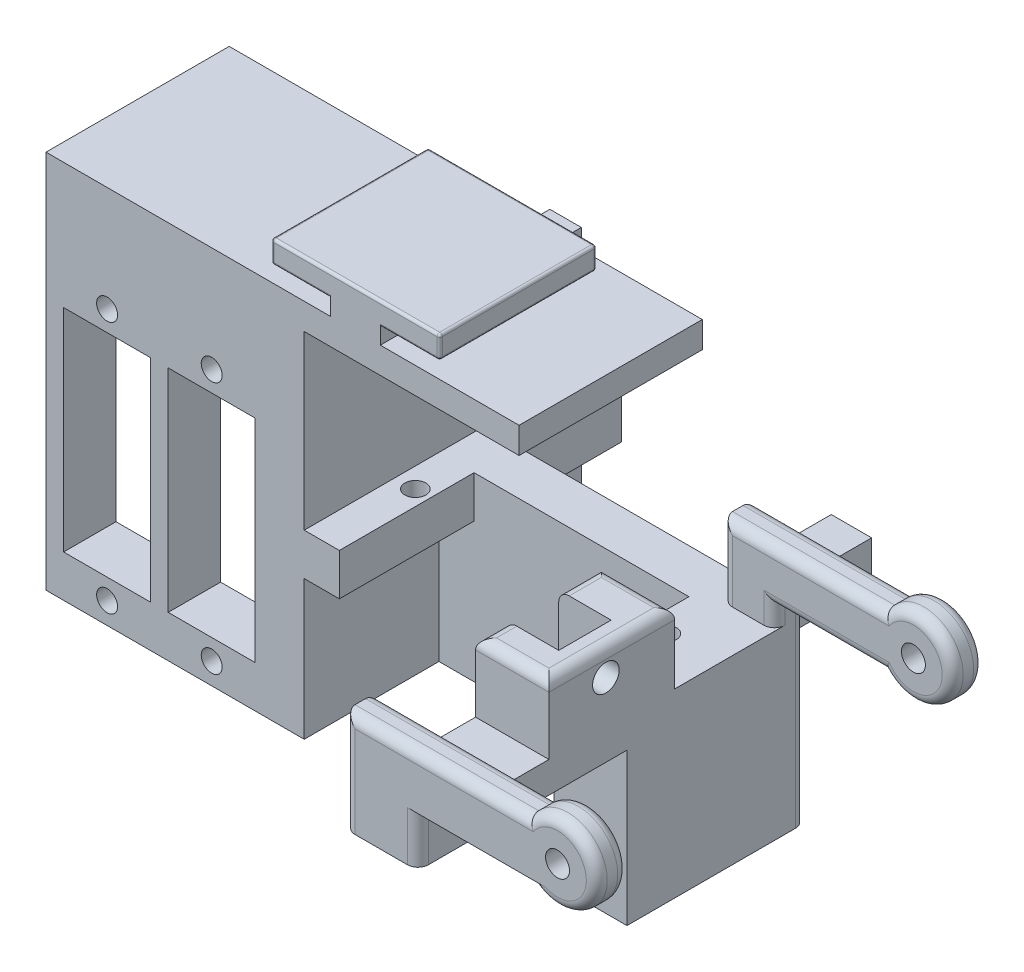
SolidWorks part; units mm, degrees
ref_plane "Front Plane" through (0, 0, 0) normal (0, 0, 1) x (1, 0, 0)
ref_plane "Top Plane" through (0, 0, 0) normal (0, 1, 0) x (1, 0, 0)
ref_plane "Right Plane" through (0, 0, 0) normal (1, 0, 0) x (0, 0, -1)
sketch "Sketch1" plane through (0, 0, 0) normal (0, 0, 1) x (1, 0, 0)
  line L1 (-10.82, 18.1) -> (10.82, 18.1)
  line L2 (-10.82, 18.1) -> (-10.82, -18.1)
  line L3 (-10.82, -18.1) -> (10.82, -18.1)
  line L4 (10.82, 18.1) -> (10.82, -18.1)
  line L5 (-10.82, 18.1) -> (10.82, -18.1) construction
  line L6 (-10.82, -18.1) -> (10.82, 18.1) construction
  point P0 (0, 0)
  dimension "D1" = 21.64
  dimension "D2" = 36.2
extrude "Center Column" add sketch "Sketch1" along normal mid plane 5
sketch "Sketch2" plane through (-10.82, 0, 0) normal (-1, 0, 0) x (0, 0, 1)
  line L0 (-2.5, 18.1) -> (-14.98, 18.1)
  line L1 (-14.98, 18.1) -> (-14.98, 15.6)
  line L2 (-14.98, 15.6) -> (-10.5, 15.6)
  line L3 (-10.5, 15.6) -> (-2.5, 10.98)
  line L4 (-2.5, 18.1) -> (-2.5, -18.1) construction
  line L6 (-2.5, 10.98) -> (2.5, 10.98)
  line L7 (2.5, 18.1) -> (2.5, -18.1) construction
  line L8 (2.5, 10.98) -> (2.5, 18.1)
  line L9 (2.5, 18.1) -> (-2.5, 18.1)
  dimension "D1" = 12.48
  dimension "D2" = 2.5
  dimension "D3" = 4.48
  dimension "D4" = 7.12
extrude "Column Cap" add sketch "Sketch2" against normal blind 55.14
sketch "Sketch5" plane through (0, 0, 2.5) normal (0, 0, 1) x (1, 0, 0)
  line L0 (16.33, 18.1) -> (21.08, 18.1)
  line L1 (44.32, 18.1) -> (-10.82, 18.1) construction
  line L2 (21.08, 18.1) -> (21.08, 19.6)
  line L3 (21.08, 19.6) -> (26.74, 19.6)
  line L4 (26.74, 19.6) -> (26.74, 21.75)
  line L5 (26.74, 21.75) -> (10.67, 21.75)
  line L6 (10.67, 21.75) -> (10.67, 19.6)
  line L7 (10.67, 19.6) -> (16.33, 19.6)
  line L8 (16.33, 19.6) -> (16.33, 18.1)
  dimension "D1" = 4.75
  dimension "D2" = 5.66
  dimension "D3" = 5.66
  dimension "D4" = 2.15
  dimension "D5" = 1.5
  dimension "D6" = 2.15
  dimension "D7" = 27.15
extrude "Attachment Block" add sketch "Sketch5" against normal blind 14.98
sketch "Sketch6" plane through (10.82, 0, 0) normal (1, 0, 0) x (0, 0, -1)
  line L0 (-2.5, -18.1) -> (-2.5, -3.6)
  line L1 (-2.5, -18.1) -> (-2.5, 10.98) construction
  line L2 (-2.5, -3.6) -> (2.5, -3.6)
  line L3 (2.5, -18.1) -> (2.5, 10.98) construction
  line L4 (2.5, -3.6) -> (2.5, -18.1)
  line L5 (2.5, -18.1) -> (-2.5, -18.1)
  dimension "D1" = 14.5
extrude "Central Extrusion" add sketch "Sketch6" along normal blind 33.792
sketch "Sketch7" plane through (0, 0, -2.5) normal (0, 0, -1) x (-1, 0, 0)
  line L0 (-10.82, -3.6) -> (-10.82, -0.8181)
  line L1 (-10.82, -3.6) -> (-10.82, 10.98) construction
  line L4 (-34.92, -0.8181) -> (-10.82, -0.8181)
  line L6 (-44.612, -18.1) -> (-10.82, -18.1)
  line L7 (10.82, -18.1) -> (-44.612, -18.1) construction
  line L8 (-10.82, -18.1) -> (-10.82, -3.6)
  line L10 (-44.612, -3.6) -> (-10.82, -3.6) construction
  line L11 (-34.92, -0.8181) -> (-44.612, -0.8181)
  line L12 (-44.612, -0.8181) -> (-44.612, -18.1)
  line L13 (-44.612, -18.1) -> (-40.254, -18.1)
  dimension "D1" = 24.1
  dimension "D2" = 2.7819
  dimension "D3" = 4.358
extrude "Wing Extrusion" add sketch "Sketch7" along normal mid plane 0.89
sketch "Sketch10" plane through (0, 0, -2.945) normal (0, 0, -1) x (-1, 0, 0)
  line L0 (-10.82, -0.8181) -> (-10.82, -9.8181)
  line L1 (-10.82, -9.8181) -> (-14.67, -9.8181)
  line L2 (-14.67, -9.8181) -> (-14.67, -0.8181)
  line L3 (-10.82, -0.8181) -> (-44.612, -0.8181) construction
  line L4 (-14.67, -0.8181) -> (-10.82, -0.8181)
  dimension "D1" = 9
  dimension "D2" = 3.85
extrude "Servo Tab Extrusion" add sketch "Sketch10" along normal blind 9.48
sketch "Sketch11" plane through (0, 0, -2.945) normal (0, 0, -1) x (-1, 0, 0)
  line L0 (-44.612, -0.8181) -> (-44.612, -18.1)
  line L1 (-14.67, -0.8181) -> (-44.612, -0.8181) construction
  line L2 (-44.612, -18.1) -> (-10.82, -18.1) construction
  line L3 (-44.612, -18.1) -> (-34.67, -18.1)
  line L4 (-34.67, -18.1) -> (-34.67, -0.8181)
  line L5 (-34.67, -0.8181) -> (-44.612, -0.8181)
  dimension "D1" = 20
  dimension "D2" = 0
extrude "Front Tab Extrusion" add sketch "Sketch11" along normal blind 11.63
sketch "Sketch15" plane through (0, 0, -2.055) normal (0, 0, 1) x (1, 0, 0)
  line L0 (37.612, -3.6) -> (47.612, -3.6)
  line L1 (10.82, -3.6) -> (44.612, -3.6) construction
  line L2 (47.612, -3.6) -> (47.612, 5.9)
  line L3 (47.612, 5.9) -> (37.612, 5.9)
  line L4 (37.612, 5.9) -> (37.612, -3.6)
  dimension "D1" = 7
  dimension "D2" = 10
  dimension "D3" = 9.5
extrude "Center Block" add sketch "Sketch15" along normal blind 12
sketch "Sketch16" plane through (37.612, 0, 0) normal (-1, 0, 0) x (0, 0, 1)
  line L0 (2.009, 5.9) -> (2.009, 0.47)
  line L1 (9.945, 5.9) -> (-2.055, 5.9) construction
  line L2 (2.009, 0.47) -> (7.009, 0.47)
  line L3 (7.009, 0.47) -> (7.009, 5.9)
  line L4 (2.009, 5.9) -> (7.009, 5.9)
  line L5 (-2.055, 5.9) -> (-2.055, -0.8181) construction
  dimension "D1" = 4.064
  dimension "D2" = 5
  dimension "D3" = 5.43
extrude "Center Chasm" cut sketch "Sketch16" against normal blind 5
sketch "Sketch17" plane through (42.612, 0, 0) normal (-1, 0, 0) x (0, 0, 1)
  line L0 (7.009, 5.9) -> (2.009, 5.9) construction
  line L1 (2.009, 5.9) -> (2.009, 0.47) construction
  circle A0 centre (4.509, 3.4) radius 1.27
  dimension "D1" = 2.54
  dimension "D2" = 2.5
  dimension "D3" = 2.5
extrude "Center Hole" cut sketch "Sketch17" against normal through all
sketch "Sketch18" plane through (0, 0, 9.945) normal (0, 0, 1) x (1, 0, 0)
  line L1 (47.612, -3.6) -> (47.612, 5.9) construction
  line L2 (47.612, -0.6488) -> (37.612, -0.6488)
  line L3 (37.612, 5.9) -> (37.612, -3.6) construction
  line L4 (37.612, -0.6488) -> (37.612, -3.6)
  line L6 (37.612, -3.6) -> (47.612, -3.6)
  line L7 (47.612, -3.6) -> (47.612, -0.6488)
  dimension "D1" = 2.9512
extrude "Holder Arm" add sketch "Sketch18" along normal blind 12.5
sketch "Sketch19" plane through (0, -0.6488, 0) normal (0, 1, 0) x (1, 0, 0)
  line L1 (37.612, -22.445) -> (37.612, -9.945) construction
  line L7 (37.612, -19.445) -> (37.612, -22.445)
  line L8 (37.612, -22.445) -> (47.612, -22.445)
  line L11 (37.612, -19.445) -> (47.612, -19.445)
  line L12 (47.612, -19.445) -> (47.612, -22.445)
  line L13 (47.612, -22.445) -> (47.612, -9.945) construction
  dimension "D1" = 3
extrude "Elbow Extrusion" add sketch "Sketch19" along normal blind 6.78
sketch "Sketch27" plane through (47.612, 0, 0) normal (1, 0, 0) x (0, 0, -1)
  line L0 (-22.445, 6.1312) -> (-22.445, 1.1312)
  line L1 (-22.445, -3.6) -> (-22.445, 6.1312) construction
  line L2 (-22.445, 1.1312) -> (-19.445, 1.1312)
  line L3 (-19.445, 6.1312) -> (-19.445, -0.6488) construction
  line L4 (-19.445, 1.1312) -> (-19.445, 6.1312)
  line L5 (-19.445, 6.1312) -> (-22.445, 6.1312)
  dimension "D1" = 5
extrude "Forearm Extrusion" add sketch "Sketch27" along normal blind 7.874
sketch "Sketch28" plane through (0, 0, 22.445) normal (0, 0, 1) x (1, 0, 0)
  circle A0 centre (57.932, 3.6312) radius 1.143
  circle A1 centre (57.932, 3.6312) radius 3.75
  dimension "D1" = 2.286
  dimension "D4" = 7.5
  dimension "D2" = 20.32
  dimension "D3" = 2.5
extrude "Hand Extrusion" add sketch "Sketch28" against normal up to surface (3 mm away) up to face at (46.9033, 2.2045, 19.445)
sketch "Sketch23" plane through (0, -0.8181, 0) normal (0, 1, 0) x (1, 0, 0)
  line L1 (44.612, 14.575) -> (39.612, 14.575)
  line L2 (44.612, 14.575) -> (44.612, 11.575)
  line L3 (44.612, 11.575) -> (39.612, 11.575)
  line L4 (39.612, 14.575) -> (39.612, 11.575)
  dimension "D1" = 5
  dimension "D2" = 3
extrude "Right Elbow Extrusion" add sketch "Sketch23" along normal blind 6.902
sketch "Sketch24" plane through (44.612, 0, 0) normal (1, 0, 0) x (0, 0, -1)
  line L0 (11.575, 6.0839) -> (14.575, 6.0839)
  line L1 (14.575, 6.0839) -> (14.575, 1.0839)
  line L2 (14.575, 6.0839) -> (14.575, -18.1) construction
  line L3 (14.575, 1.0839) -> (11.575, 1.0839)
  line L4 (11.575, 6.0839) -> (11.575, -0.8181) construction
  line L5 (11.575, 1.0839) -> (11.575, 6.0839)
  dimension "D1" = 5
extrude "Right Forearm Extrusion" add sketch "Sketch24" along normal blind 11
sketch "Sketch25" plane through (0, 0, -14.575) normal (0, 0, -1) x (-1, 0, 0)
  line L1 (-34.67, -18.1) -> (-34.67, -0.8181) construction
  circle A0 centre (-57.87, 3.5839) radius 1.143
  circle A1 centre (-57.87, 3.5839) radius 3.75
  dimension "D2" = 2.286
  dimension "D4" = 7.5
  dimension "D1" = 23.2
  dimension "D3" = 2.5
extrude "Right Hand" add sketch "Sketch25" against normal up to surface (3 mm away) up to face at (46.612, 2.1166, -11.575)
sketch "Sketch26" plane through (0, 0, -2.5) normal (0, 0, -1) x (-1, 0, 0)
  line L0 (10.82, 10.98) -> (10.82, -18.1) construction
  line L1 (0.84, 6.1) -> (9.14, 6.1)
  line L2 (0.84, 6.1) -> (0.84, -14.1)
  line L3 (0.84, -14.1) -> (9.14, -14.1)
  line L4 (9.14, 6.1) -> (9.14, -14.1)
  line L5 (-9.14, 6.1) -> (-0.84, 6.1)
  line L6 (-9.14, 6.1) -> (-9.14, -14.1)
  line L7 (-9.14, -14.1) -> (-0.84, -14.1)
  line L8 (-0.84, 6.1) -> (-0.84, -14.1)
  line L9 (10.82, 10.98) -> (-10.82, 10.98) construction
  circle A0 centre (-4.99, 8.05) radius 1
  circle A1 centre (4.99, 8.05) radius 1
  circle A2 centre (-4.99, -16.05) radius 1
  circle A3 centre (4.99, -16.05) radius 1
  dimension "D9" = 2
  dimension "D10" = 2
  dimension "D11" = 2
  dimension "D12" = 2
  dimension "D1" = 1.68
  dimension "D2" = 4.88
  dimension "D3" = 20.2
  dimension "D4" = 8.3
  dimension "D5" = 1.68
  dimension "D6" = 8.3
  dimension "D7" = 4.88
  dimension "D8" = 20.2
  dimension "D13" = 4.15
  dimension "D14" = 1.95
  dimension "D15" = 1.95
  dimension "D16" = 4.15
  dimension "D17" = 1.95
  dimension "D18" = 4.15
  dimension "D19" = 1.95
  dimension "D20" = 4.15
extrude "Rear Servo Mounts" cut sketch "Sketch26" against normal through all
sketch "Sketch29" plane through (10.82, 0, 0) normal (1, 0, 0) x (0, 0, -1)
  line L1 (-2.5, 10.98) -> (19.745, 10.98)
  line L2 (2.945, -18.1) -> (19.745, -18.1)
  line L3 (19.745, -18.1) -> (19.745, 10.98)
  line L4 (-2.5, 10.98) -> (-2.5, -18.1)
  line L5 (-2.5, -18.1) -> (2.945, -18.1)
  dimension "D2" = 16.8
extrude "New Back" add sketch "Sketch29" along normal blind 3
sketch "Sketch30" plane through (0, -18.1, 0) normal (0, -1, 0) x (1, 0, 0)
  line L10 (10.82, -19.745) -> (13.82, -19.745)
  line L11 (10.82, -19.745) -> (13.82, -19.745)
  line L12 (13.82, -19.745) -> (13.82, -2.945)
  line L13 (13.82, -19.745) -> (13.82, -2.945)
  line L14 (44.612, 2.5) -> (-10.82, 2.5)
  line L19 (-10.82, 2.5) -> (-10.82, -2.5)
  line L20 (-10.82, -2.5) -> (10.82, -2.5)
  line L21 (10.82, -2.5) -> (10.82, -19.745)
  line L24 (13.82, -2.945) -> (34.67, -2.945)
  line L25 (34.67, -2.945) -> (34.67, -14.575)
  line L26 (34.67, -14.575) -> (44.612, -14.575)
  line L27 (44.612, -14.575) -> (44.612, 2.5)
  line L28 (44.612, 2.5) -> (-10.82, 2.5)
  line L33 (-10.82, 2.5) -> (-10.82, -2.5)
  line L34 (-10.82, -2.5) -> (10.82, -2.5)
  line L35 (10.82, -2.5) -> (10.82, -19.745)
  line L38 (13.82, -2.945) -> (34.67, -2.945)
  line L39 (34.67, -2.945) -> (34.67, -14.575)
  line L40 (34.67, -14.575) -> (44.612, -14.575)
  line L41 (44.612, -14.575) -> (44.612, 2.5)
  dimension "D1" = 0
extrude "Bottom Support" add sketch "Sketch30" along normal blind 3
sketch "Sketch31" plane through (34.67, 0, 0) normal (-1, 0, 0) x (0, 0, 1)
  line L0 (-14.575, -0.8181) -> (-2.945, -0.8181)
  line L1 (-2.945, -0.8181) -> (-2.945, -21.1)
  line L2 (-2.945, -21.1) -> (-14.575, -21.1)
  line L3 (-14.575, -21.1) -> (-14.575, -0.8181)
extrude "Re-cut Central Cavity" cut sketch "Sketch31" against normal blind 3
sketch "Sketch32" plane through (14.67, 0, 0) normal (1, 0, 0) x (0, 0, -1)
  line L4 (2.945, -0.8181) -> (2.945, -9.8181)
  line L5 (2.945, -9.8181) -> (12.425, -9.8181)
  line L6 (12.425, -9.8181) -> (12.425, -0.8181)
  line L7 (12.425, -0.8181) -> (2.945, -0.8181)
  line L8 (2.945, -0.8181) -> (2.945, -9.8181)
  line L9 (2.945, -9.8181) -> (12.425, -9.8181)
  line L10 (12.425, -9.8181) -> (12.425, -0.8181)
  line L11 (12.425, -0.8181) -> (2.945, -0.8181)
  dimension "D1" = 0
extrude "Form Left Front-Rear Block" add sketch "Sketch32" along normal blind 3
sketch "Sketch33" plane through (0, 0, -2.945) normal (0, 0, -1) x (-1, 0, 0)
  line L0 (-37.67, -0.8181) -> (-37.67, -18.1)
  line L1 (-37.67, -21.1) -> (-37.67, -0.8181) construction
  line L2 (-37.67, -0.8181) -> (-17.67, -0.8181)
  line L3 (-17.67, -0.8181) -> (-17.67, -18.1)
  line L4 (-17.67, -18.1) -> (-37.67, -18.1)
  dimension "D1" = 3
extrude "Create Center Cavity" cut sketch "Sketch33" against normal through all
sketch "Sketch34" plane through (13.82, 0, 0) normal (1, 0, 0) x (0, 0, -1)
  line L0 (12.425, -0.8181) -> (2.055, -0.8181) construction
  line L1 (12.425, -0.8181) -> (10.355, -0.8181)
  line L2 (12.425, -0.8181) -> (12.425, -21.1)
  line L6 (10.355, -0.8181) -> (10.355, -21.1)
  line L7 (19.745, -21.1) -> (2.945, -21.1) construction
  line L8 (10.355, -21.1) -> (12.425, -21.1)
  dimension "D1" = 8.3
  dimension "D2" = 0
extrude "Boss-Extrude6" add sketch "Sketch34" along normal up to surface (23.85 mm away) up to face at (37.67, -9.7838, 1.4217)
sketch "Sketch35" plane through (0, 0, -12.425) normal (0, 0, -1) x (-1, 0, 0)
  line L0 (-13.82, -0.8181) -> (-13.82, -21.1)
  line L4 (-13.82, 10.98) -> (-13.82, -0.8181)
  line L6 (-13.82, 10.98) -> (-10.82, 10.98)
  line L7 (-10.82, 10.98) -> (-10.82, -21.1)
  line L8 (-10.82, -21.1) -> (-13.82, -21.1)
  dimension "D1" = 3
extrude "Extend Wing Extrusion" add sketch "Sketch35" along normal blind 10.6532
sketch "Sketch37" plane through (0, 0, -12.425) normal (0, 0, -1) x (-1, 0, 0)
  line L0 (-13.82, -0.8181) -> (-13.82, -9.8181)
  line L1 (-13.82, -21.1) -> (-13.82, -0.8181) construction
  line L2 (-13.82, -9.8181) -> (-17.67, -9.8181)
  line L3 (-17.67, -9.8181) -> (-17.67, -0.8181)
  line L4 (-13.82, -0.8181) -> (-37.67, -0.8181) construction
  line L5 (-17.67, -0.8181) -> (-13.82, -0.8181)
  dimension "D1" = 9
  dimension "D2" = 3.85
extrude "Right Front-Rear Extrusion" add sketch "Sketch37" along normal blind 9.48
sketch "Sketch38" plane through (0, 5.9, 0) normal (0, 1, 0) x (1, 0, 0)
  line L0 (47.612, -9.945) -> (47.612, 2.055)
  line L1 (47.612, 2.055) -> (44.612, 2.055)
  line L2 (47.612, 2.055) -> (37.612, 2.055) construction
  line L3 (44.612, 2.055) -> (44.612, -9.945)
  line L4 (47.612, -9.945) -> (37.612, -9.945) construction
  line L5 (44.612, -9.945) -> (47.612, -9.945)
  dimension "D1" = 3
extrude "Trim Center Block" cut sketch "Sketch38" against normal up to surface (6.5488 mm away) up to face at (42.612, -0.6488, 14.695)
sketch "Sketch39" plane through (0, 0, -14.575) normal (0, 0, -1) x (-1, 0, 0)
  line L0 (-37.67, -0.8181) -> (-37.67, -9.8181)
  line L1 (-37.67, -0.8181) -> (-37.67, -21.1) construction
  line L2 (-37.67, -9.8181) -> (-41.52, -9.8181)
  line L3 (-41.52, -9.8181) -> (-41.52, -0.8181)
  line L4 (-41.52, -0.8181) -> (-37.67, -0.8181)
  dimension "D1" = 9
  dimension "D2" = 3.85
extrude "Right Front Extension" add sketch "Sketch39" along normal up to surface (7.33 mm away) up to face at (15.745, -5.3181, -21.905)
sketch "Sketch40" plane through (0, -3.6, 0) normal (0, -1, 0) x (1, 0, 0)
  line L0 (44.612, 2.5) -> (44.612, -2.055)
  line L1 (44.612, -2.055) -> (47.612, -2.055)
  line L2 (47.612, -2.055) -> (47.612, 22.445)
  line L3 (47.612, 22.445) -> (44.612, 22.445)
  line L4 (37.67, 22.445) -> (47.612, 22.445) construction
  line L5 (44.612, 22.445) -> (44.612, 2.5)
extrude "Trim Left Arm" cut sketch "Sketch40" against normal up to surface (4.7312 mm away) up to face at (51.3745, 1.1312, 20.945)
sketch "Sketch42" plane through (0, 0, -2.945) normal (0, 0, -1) x (-1, 0, 0)
  line L0 (-37.67, -21.1) -> (-37.67, -18.1)
  line L1 (-37.67, -18.1) -> (-13.82, -18.1)
  line L2 (-13.82, -9.8181) -> (-13.82, -21.1) construction
  line L3 (-13.82, -18.1) -> (-13.82, -21.1)
  line L4 (-13.82, -21.1) -> (-37.67, -21.1)
extrude "Close Base Plate" add sketch "Sketch42" along normal up to surface (7.41 mm away) up to face at (23.0533, -10.5787, -10.355)
sketch "Sketch43" plane through (17.67, 0, 0) normal (1, 0, 0) x (0, 0, -1)
  line L0 (2.945, -9.8181) -> (-2.5, -9.8181)
  line L1 (-2.5, -3.6) -> (-2.5, -18.1) construction
  line L2 (-2.5, -9.8181) -> (-2.5, -18.1)
  line L3 (-2.5, -18.1) -> (2.945, -18.1)
  line L4 (2.945, -18.1) -> (2.945, -9.8181)
extrude "Shape Left Front Block" cut sketch "Sketch43" against normal up to surface (3.85 mm away) up to face at (13.82, -13.9591, -6.65)
sketch "Sketch44" plane through (0, -3.6, 0) normal (0, 1, 0) x (1, 0, 0)
  line L4 (13.82, -2.5) -> (17.67, -2.5)
  line L5 (17.67, -2.5) -> (17.67, 2.055)
  line L6 (17.67, 2.055) -> (13.82, 2.055)
  line L7 (13.82, 2.055) -> (13.82, -2.5)
  line L8 (13.82, -2.5) -> (17.67, -2.5)
  line L9 (17.67, -2.5) -> (17.67, 2.055)
  line L10 (17.67, 2.055) -> (13.82, 2.055)
  line L11 (13.82, 2.055) -> (13.82, -2.5)
  dimension "D1" = 0
extrude "Fix Left Front Chip" add sketch "Sketch44" along normal up to surface (2.7819 mm away) up to face at (31.2805, -0.8181, -12.1063)
sketch "Sketch45" plane through (0, 0, -21.905) normal (0, 0, -1) x (-1, 0, 0)
  line L0 (-13.82, -9.8181) -> (-13.82, -21.1)
  line L4 (-41.52, -0.8181) -> (-41.52, -9.8181)
  line L5 (-41.52, -9.8181) -> (-37.67, -9.8181)
  line L6 (-37.67, -9.8181) -> (-37.67, -0.8181)
  line L7 (-37.67, -0.8181) -> (-41.52, -0.8181)
  line L8 (-41.52, -0.8181) -> (-41.52, -9.8181)
  line L9 (-41.52, -9.8181) -> (-37.67, -9.8181)
  line L10 (-37.67, -9.8181) -> (-37.67, -0.8181)
  line L11 (-37.67, -0.8181) -> (-41.52, -0.8181)
  line L12 (-13.82, -0.8181) -> (-17.67, -0.8181)
  line L13 (-17.67, -0.8181) -> (-17.67, -9.8181)
  line L14 (-17.67, -9.8181) -> (-13.82, -9.8181)
  line L15 (-13.82, -9.8181) -> (-13.82, -0.8181)
  line L16 (-13.82, -0.8181) -> (-17.67, -0.8181)
  line L17 (-17.67, -0.8181) -> (-17.67, -9.8181)
  line L18 (-17.67, -9.8181) -> (-13.82, -9.8181)
  line L22 (-13.82, 10.98) -> (-13.82, -21.1)
  line L25 (-13.82, -21.1) -> (-10.82, -21.1)
  line L26 (-10.82, -21.1) -> (-10.82, 10.98)
  line L27 (-10.82, 10.98) -> (-13.82, 10.98)
  line L28 (-13.82, 10.98) -> (-13.82, -0.8181)
  line L31 (-13.82, -21.1) -> (-10.82, -21.1)
  line L32 (-10.82, -21.1) -> (-10.82, 10.98)
  line L33 (-10.82, 10.98) -> (-13.82, 10.98)
  dimension "D1" = 0
  dimension "D2" = 0
  dimension "D3" = 0
extrude "Adjust Front Mounting Block" add sketch "Sketch45" along normal blind 2.032
sketch "Sketch46" plane through (0, 0, -12.425) normal (0, 0, -1) x (-1, 0, 0)
  line L6 (-17.67, -9.8181) -> (-17.67, -0.8181)
  line L7 (-17.67, -0.8181) -> (-37.67, -0.8181)
  line L8 (-37.67, -0.8181) -> (-37.67, -21.1)
  line L9 (-37.67, -21.1) -> (-13.82, -21.1)
  line L10 (-13.82, -21.1) -> (-13.82, -9.8181)
  line L11 (-13.82, -9.8181) -> (-17.67, -9.8181)
  line L12 (-17.67, -9.8181) -> (-17.67, -0.8181)
  line L13 (-17.67, -0.8181) -> (-37.67, -0.8181)
  line L14 (-37.67, -0.8181) -> (-37.67, -21.1)
  line L15 (-37.67, -21.1) -> (-13.82, -21.1)
  line L16 (-13.82, -21.1) -> (-13.82, -9.8181)
  line L17 (-13.82, -9.8181) -> (-17.67, -9.8181)
  dimension "D1" = 0
extrude "Thicken Center Block" add sketch "Sketch46" along normal up to surface (2.15 mm away)
sketch "Sketch47" plane through (0, -0.8181, 0) normal (0, 1, 0) x (1, 0, 0)
  line L1 (37.67, 14.575) -> (37.67, 23.937) construction
  line L2 (17.67, 23.937) -> (17.67, 14.575) construction
  line L3 (37.67, 2.055) -> (37.67, 10.355) construction
  line L4 (17.67, 10.355) -> (17.67, -2.5) construction
  circle A0 centre (39.62, 18.725) radius 1
  circle A1 centre (15.72, 18.725) radius 1
  circle A2 centre (15.72, 6.205) radius 1
  circle A3 centre (39.62, 6.205) radius 1
  dimension "D1" = 2
  dimension "D2" = 2
  dimension "D3" = 2
  dimension "D4" = 2
  dimension "D5" = 4.15
  dimension "D6" = 4.15
  dimension "D7" = 4.15
  dimension "D8" = 4.15
  dimension "D9" = 1.95
  dimension "D10" = 1.95
  dimension "D11" = 1.95
  dimension "D12" = 1.95
extrude "Front Servo Mounts" cut sketch "Sketch47" against normal up to surface (9 mm away) up to face at (15.745, -9.8181, -3.9275)
fillet "Hand Fillets" radius 1 19 edges at (61.682, 3.6312, 19.445) (61.682, 3.6312, 22.445) (46.3745, 6.1312, 22.445) (37.612, 2.6565, 22.445) (44.612, -1.2344, 22.445) (37.612, 2.7412, 19.445) (46.3745, 6.1312, 19.445) (49.8745, 1.1312, 19.445) (44.612, 0.2412, 19.445) (39.612, 2.6329, -11.575) (44.612, 0.1329, -11.575) (49.8435, 1.0839, -11.575) (47.3435, 6.0839, -11.575) (61.62, 3.5839, -11.575) (44.612, -10.0081, -14.575) (39.612, 2.6329, -14.575) (49.8435, 1.0839, -14.575) (61.62, 3.5839, -14.575) (47.3435, 6.0839, -14.575)
fillet "Center Block Fillet" radius 1 5 edges at (41.112, 5.9, -2.055) (37.612, 5.9, 8.477) (37.612, 5.9, -0.023) (44.612, 5.9, 3.945) (41.112, 5.9, 9.945)
sketch "Sketch48" plane through (-10.82, 0, 0) normal (-1, 0, 0) x (0, 0, 1)
  line L0 (-10.5, 15.6) -> (-2.5, 10.98)
  line L1 (-2.5, 10.98) -> (-2.5, 15.6)
  line L2 (-2.5, 15.6) -> (-10.5, 15.6)
extrude "Cut-Extrude1" cut sketch "Sketch48" against normal up to surface (55.14 mm away) up to face at (44.32, 14.8933, -6.3267)
sketch "Sketch49" plane through (44.32, 0, 0) normal (1, 0, 0) x (0, 0, -1)
  line L0 (-2.5, 10.98) -> (2.5, 10.98)
  line L1 (2.5, 10.98) -> (2.5, 13.29)
  line L2 (2.5, 15.6) -> (2.5, 10.98) construction
  line L3 (2.5, 13.29) -> (-2.5, 13.29)
  line L4 (-2.5, 10.98) -> (-2.5, 18.1) construction
  line L5 (-2.5, 13.29) -> (-2.5, 10.98)
extrude "Cut-Extrude2" cut sketch "Sketch49" against normal up to vertex
sketch "Sketch50" plane through (44.32, 0, 0) normal (1, 0, 0) x (0, 0, -1)
  line L6 (-2.5, 18.1) -> (-2.5, 13.29)
  line L7 (-2.5, 13.29) -> (2.5, 13.29)
  line L8 (2.5, 13.29) -> (2.5, 15.6)
  line L9 (2.5, 15.6) -> (14.98, 15.6)
  line L10 (14.98, 15.6) -> (14.98, 18.1)
  line L11 (14.98, 18.1) -> (-2.5, 18.1)
  line L12 (-2.5, 18.1) -> (-2.5, 13.29)
  line L13 (-2.5, 13.29) -> (2.5, 13.29)
  line L14 (2.5, 13.29) -> (2.5, 15.6)
  line L15 (2.5, 15.6) -> (14.98, 15.6)
  line L16 (14.98, 15.6) -> (14.98, 18.1)
  line L17 (14.98, 18.1) -> (-2.5, 18.1)
  dimension "D1" = 0
extrude "Cut-Extrude3" cut sketch "Sketch50" against normal blind 10
sketch "Sketch51" plane through (0, 0, -14.575) normal (0, 0, -1) x (-1, 0, 0)
  circle A0 centre (-57.87, 3.5839) radius 3.75
  dimension "D1" = 7.5
sketch "Sketch52" plane through (0, -21.1, 0) normal (0, -1, 0) x (1, 0, 0)
  line L8 (13.82, -14.575) -> (43.612, -14.575)
  line L9 (44.612, -13.575) -> (44.612, 2.5)
  line L10 (44.612, 2.5) -> (-10.82, 2.5)
  line L11 (-10.82, 2.5) -> (-10.82, -2.5)
  line L12 (-10.82, -2.5) -> (10.82, -2.5)
  line L13 (10.82, -2.5) -> (10.82, -23.937)
  line L14 (10.82, -23.937) -> (13.82, -23.937)
  line L15 (13.82, -23.937) -> (13.82, -14.575)
  line L16 (13.82, -14.575) -> (43.612, -14.575)
  line L17 (44.612, -13.575) -> (44.612, 2.5)
  line L18 (44.612, 2.5) -> (-10.82, 2.5)
  line L19 (-10.82, 2.5) -> (-10.82, -2.5)
  line L20 (-10.82, -2.5) -> (10.82, -2.5)
  line L21 (10.82, -2.5) -> (10.82, -23.937)
  line L22 (10.82, -23.937) -> (13.82, -23.937)
  line L23 (13.82, -23.937) -> (13.82, -14.575)
  arc A1 (43.612, -14.575) -> (44.612, -13.575) centre (43.612, -13.575) ccw
  arc A2 (43.612, -14.575) -> (44.612, -13.575) centre (43.612, -13.575) ccw
  dimension "D1" = 0
extrude "Cut-Extrude5" cut sketch "Sketch52" against normal blind 3
sketch "Sketch53" plane through (34.32, 0, 0) normal (1, 0, 0) x (0, 0, -1)
  line L0 (2.5, 15.6) -> (2.5, 13.29)
  line L1 (2.5, 13.29) -> (-2.5, 13.29)
  line L2 (-2.5, 13.29) -> (-2.5, 15.6)
  line L3 (-2.5, 18.1) -> (-2.5, 13.29) construction
  line L4 (-2.5, 15.6) -> (2.5, 15.6)
extrude "Cut-Extrude6" cut sketch "Sketch53" against normal up to surface (20.5 mm away) up to face at (13.82, -13.9591, -19.256)
fillet "Fillet3" radius 0.25 14 edges at (10.67, 20.675, -12.48) (13.5, 19.6, -12.48) (23.91, 19.6, -12.48) (26.74, 20.675, -12.48) (18.705, 21.75, -12.48) (26.74, 20.675, 2.5) (23.91, 19.6, 2.5) (13.5, 19.6, 2.5) (18.705, 21.75, 2.5) (10.67, 20.675, 2.5) (10.67, 19.6, -4.99) (10.67, 21.75, -4.99) (26.74, 19.6, -4.99) (26.74, 21.75, -4.99)
sketch "Sketch54" plane through (0, -9.8181, 0) normal (0, -1, 0) x (1, 0, 0)
  line L4 (37.67, -14.575) -> (37.67, -23.937)
  line L5 (37.67, -23.937) -> (41.52, -23.937)
  line L6 (41.52, -23.937) -> (41.52, -14.575)
  line L7 (41.52, -14.575) -> (37.67, -14.575)
  line L8 (37.67, -14.575) -> (37.67, -23.937)
  line L9 (37.67, -23.937) -> (41.52, -23.937)
  line L10 (41.52, -23.937) -> (41.52, -14.575)
  line L11 (41.52, -14.575) -> (37.67, -14.575)
  line L12 (17.67, -23.937) -> (17.67, -14.575)
  line L13 (17.67, -14.575) -> (13.82, -14.575)
  line L14 (13.82, -14.575) -> (13.82, -23.937)
  line L15 (13.82, -23.937) -> (17.67, -23.937)
  line L16 (17.67, -23.937) -> (17.67, -14.575)
  line L17 (17.67, -14.575) -> (13.82, -14.575)
  line L18 (13.82, -14.575) -> (13.82, -23.937)
  line L19 (13.82, -23.937) -> (17.67, -23.937)
  line L20 (13.82, -10.355) -> (17.67, -10.355)
  line L21 (17.67, -10.355) -> (17.67, 2.5)
  line L22 (17.67, 2.5) -> (13.82, 2.5)
  line L23 (13.82, 2.5) -> (13.82, -10.355)
  line L24 (13.82, -10.355) -> (17.67, -10.355)
  line L25 (17.67, -10.355) -> (17.67, 2.5)
  line L26 (17.67, 2.5) -> (13.82, 2.5)
  line L27 (13.82, 2.5) -> (13.82, -10.355)
  dimension "D1" = 0
  dimension "D2" = 0
  dimension "D3" = 0
extrude "Cut-Extrude9" cut sketch "Sketch54" against normal blind 5
sketch "Sketch55" plane through (17.67, 0, 0) normal (1, 0, 0) x (0, 0, -1)
  line L4 (-2.5, -0.8181) -> (-2.5, -4.8181)
  line L5 (-2.5, -4.8181) -> (10.355, -4.8181)
  line L6 (10.355, -4.8181) -> (10.355, -0.8181)
  line L7 (10.355, -0.8181) -> (-2.5, -0.8181)
  line L8 (-2.5, -0.8181) -> (-2.5, -4.8181)
  line L9 (-2.5, -4.8181) -> (10.355, -4.8181)
  line L10 (10.355, -4.8181) -> (10.355, -0.8181)
  line L11 (10.355, -0.8181) -> (-2.5, -0.8181)
  dimension "D1" = 0
extrude "Cut-Extrude10" cut sketch "Sketch55" against normal blind 0.5
